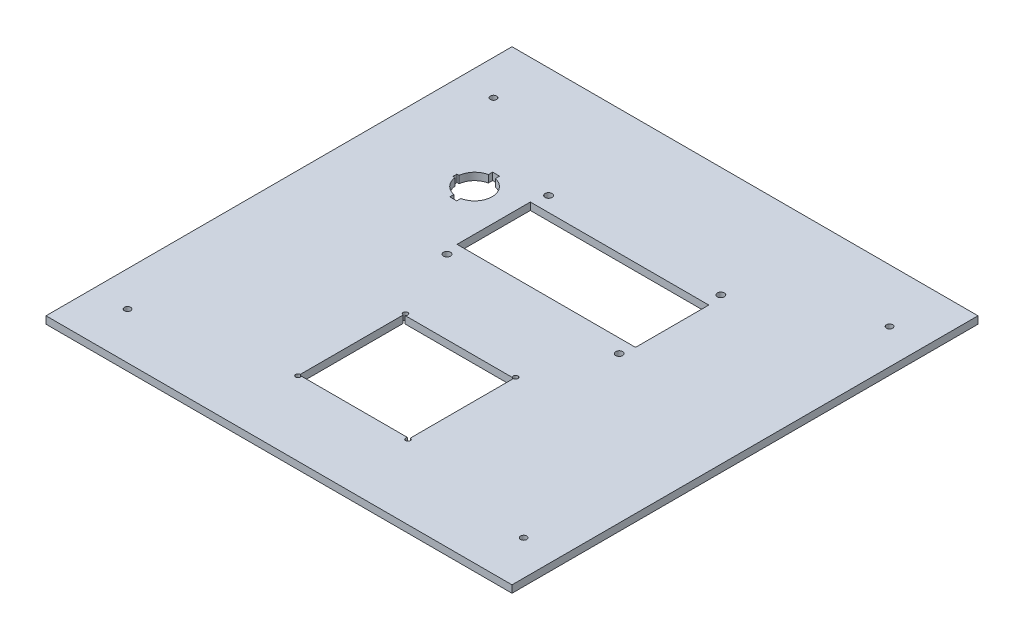
SolidWorks part; units mm, degrees
ref_plane "Front Plane" through (0, 0, 0) normal (0, 0, 1) x (1, 0, 0)
ref_plane "Top Plane" through (0, 0, 0) normal (0, 1, 0) x (1, 0, 0)
ref_plane "Right Plane" through (0, 0, 0) normal (1, 0, 0) x (0, 0, -1)
sketch "Sketch1" plane through (0, 0, 0) normal (0, 1, 0) x (1, 0, 0)
  line L4 (155.575, 0) -> (155.163, 41.0845) construction
  line L5 (155.163, 41.0845) -> (184.5403, 41.0845)
  line L6 (155.163, 41.0845) -> (126.6023, 41.0845)
  line L7 (125.5395, 41.6193) -> (125.5395, 97.6997)
  line L8 (126.3634, 97.9805) -> (184.7866, 97.9805)
  line L9 (185.6105, 97.6997) -> (185.6105, 41.5897)
  line L10 (28.575, 254) -> (66.675, 254) construction
  line L11 (155.575, 69.6595) -> (282.575, 69.6595) construction
  line L19 (28.575, 254) -> (155.575, 254) construction
  line L25 (28.575, 0) -> (282.575, 0)
  line L31 (282.575, 254) -> (244.475, 254) construction
  line L33 (28.575, 254) -> (28.575, 215.9)
  line L39 (28.575, 215.9) -> (66.675, 215.9) construction
  line L40 (66.675, 215.9) -> (66.675, 254) construction
  line L41 (28.575, 254) -> (282.575, 254)
  line L42 (47.625, 215.9) -> (47.625, 224.853) construction
  line L43 (47.625, 224.853) -> (47.625, 241.2472) construction
  line L44 (28.575, 0) -> (66.675, 0) construction
  line L45 (66.675, 0) -> (66.675, 38.1) construction
  line L46 (66.675, 38.1) -> (28.575, 38.1) construction
  line L47 (47.625, 0) -> (47.625, 8.89) construction
  line L48 (47.625, 8.89) -> (47.625, 25.4) construction
  line L49 (282.575, 0) -> (282.575, 38.1) construction
  line L50 (282.575, 38.1) -> (244.475, 38.1) construction
  line L51 (244.475, 38.1) -> (244.475, 0) construction
  line L52 (244.475, 0) -> (263.525, 0) construction
  line L53 (263.525, 0) -> (263.525, 8.89) construction
  line L54 (263.525, 8.89) -> (263.525, 25.4) construction
  line L55 (282.575, 254) -> (244.475, 254) construction
  line L56 (244.475, 254) -> (244.475, 215.9) construction
  line L57 (244.475, 215.9) -> (282.575, 215.9) construction
  line L58 (263.525, 215.9) -> (263.525, 224.853) construction
  line L59 (263.525, 224.853) -> (263.525, 241.2472) construction
  line L60 (155.575, 254) -> (155.575, 196.1024) construction
  line L61 (84.3823, 177.8) -> (84.3823, 189.5342) construction
  line L62 (84.3823, 189.5342) -> (86.2873, 189.5342)
  line L63 (86.2873, 189.5342) -> (86.2873, 187.1974)
  line L64 (84.3823, 189.5342) -> (82.4773, 189.5342)
  line L65 (82.4773, 189.5342) -> (82.4773, 187.1974)
  line L66 (84.3823, 177.8) -> (84.3823, 166.1795) construction
  line L67 (84.3823, 166.1795) -> (86.2873, 166.1795)
  line L68 (28.575, 254) -> (28.575, 190.5) construction
  line L69 (28.575, 0) -> (28.575, 63.5) construction
  line L70 (28.575, 254) -> (28.575, 0)
  line L71 (28.575, 190.5) -> (30.607, 190.5) construction
  line L72 (86.2873, 166.1795) -> (86.2873, 168.4026)
  line L73 (84.3823, 166.1795) -> (82.4773, 166.1795)
  line L74 (82.4773, 166.1795) -> (82.4773, 168.4026)
  line L75 (84.3823, 177.8) -> (74.7938, 177.8) construction
  line L76 (74.7938, 177.8) -> (73.7016, 177.8) construction
  line L77 (73.7016, 177.8) -> (73.7016, 178.8668)
  line L78 (73.7016, 178.8668) -> (74.8533, 178.8668)
  line L79 (73.7016, 177.8) -> (73.7016, 176.7332)
  line L80 (73.7016, 176.7332) -> (74.8533, 176.7332)
  line L87 (282.575, 254) -> (282.575, 193.4845) construction
  line L89 (282.575, 0) -> (282.575, 66.5095) construction
  line L91 (282.575, 254) -> (282.575, 0)
  line L106 (155.575, 185.6994) -> (155.575, 196.1024) construction
  line L107 (155.575, 196.1024) -> (204.978, 196.1024) construction
  line L108 (155.575, 185.6994) -> (204.1525, 185.6994)
  line L109 (204.1525, 185.6994) -> (204.1525, 145.7452)
  line L110 (155.575, 185.6994) -> (106.8705, 185.6994)
  line L111 (106.8705, 185.6994) -> (106.8705, 145.7452)
  line L112 (106.8705, 145.7452) -> (204.1525, 145.7452)
  line L113 (204.978, 196.1024) -> (204.978, 136.0314) construction
  line L114 (204.978, 136.0314) -> (106.426, 136.0314) construction
  line L115 (155.575, 196.1024) -> (106.426, 196.1024) construction
  line L116 (106.426, 196.1024) -> (106.426, 136.0314) construction
  line L117 (204.978, 196.1024) -> (202.6431, 193.7675) construction
  line L118 (106.426, 196.1024) -> (108.7609, 193.7675) construction
  line L119 (106.426, 136.0314) -> (108.7609, 138.3663) construction
  line L120 (204.978, 136.0314) -> (202.6431, 138.3663) construction
  line L122 (155.575, 101.6635) -> (188.2775, 101.6635) construction
  line L123 (155.575, 101.6635) -> (122.8725, 101.6635) construction
  line L124 (122.8725, 101.6635) -> (122.8725, 37.6555) construction
  line L125 (122.8725, 37.6555) -> (188.2775, 37.6555) construction
  line L126 (188.2775, 37.6555) -> (188.2775, 101.6635) construction
  line L127 (188.2775, 101.6635) -> (185.5834, 98.9694) construction
  line L128 (122.8725, 101.6635) -> (125.5666, 98.9694) construction
  line L129 (122.8725, 37.6555) -> (125.5666, 40.3496) construction
  line L130 (188.2775, 37.6555) -> (185.5551, 40.3209) construction
  circle A20 centre (202.6431, 193.7675) radius 1.905
  circle A21 centre (108.7609, 193.7675) radius 1.905
  circle A22 centre (108.7609, 138.3663) radius 1.905
  circle A23 centre (202.6431, 138.3663) radius 1.905
  circle A24 centre (185.5834, 98.9694) radius 1.27
  circle A25 centre (125.5666, 98.9694) radius 1.27
  circle A26 centre (125.5666, 40.3496) radius 1.27
  circle A27 centre (185.5551, 40.3209) radius 1.27
  circle A29 centre (47.625, 224.853) radius 1.6891
  circle A31 centre (47.625, 25.4) radius 1.6891
  circle A33 centre (263.525, 25.4) radius 1.6891
  circle A35 centre (263.525, 224.853) radius 1.6891
  arc A38 (74.8533, 176.7332) -> (82.4773, 168.4026) centre (84.3823, 177.8) ccw
  arc A40 (82.4773, 187.1974) -> (74.8533, 178.8668) centre (84.3823, 177.8) ccw
  arc A41 (86.2873, 168.4026) -> (86.2873, 187.1974) centre (84.3823, 177.8) ccw
  dimension "D1" = 97.282
  dimension "D6" = 3.81
  dimension "D7" = 38.1
  dimension "D13" = 38.1
  dimension "D17" = 76.2
  dimension "D20" = 2.54
  dimension "D21" = 2.54
  dimension "D22" = 2.54
  dimension "D16" = 2.54
  dimension "D19" = 2.3368
  dimension "D2" = 98.552
  dimension "D3" = 39.9542
  dimension "D4" = 60.071
  dimension "D5" = 3.302
  dimension "D8" = 38.1
  dimension "D9" = 254
  dimension "D10" = 254
  dimension "D11" = 65.405
  dimension "D12" = 64.008
  dimension "D14" = 3.81
  dimension "D15" = 38.1
  dimension "D18" = 55.8073
extrude "Boss-Extrude1" add sketch "Sketch1" along normal blind 4
